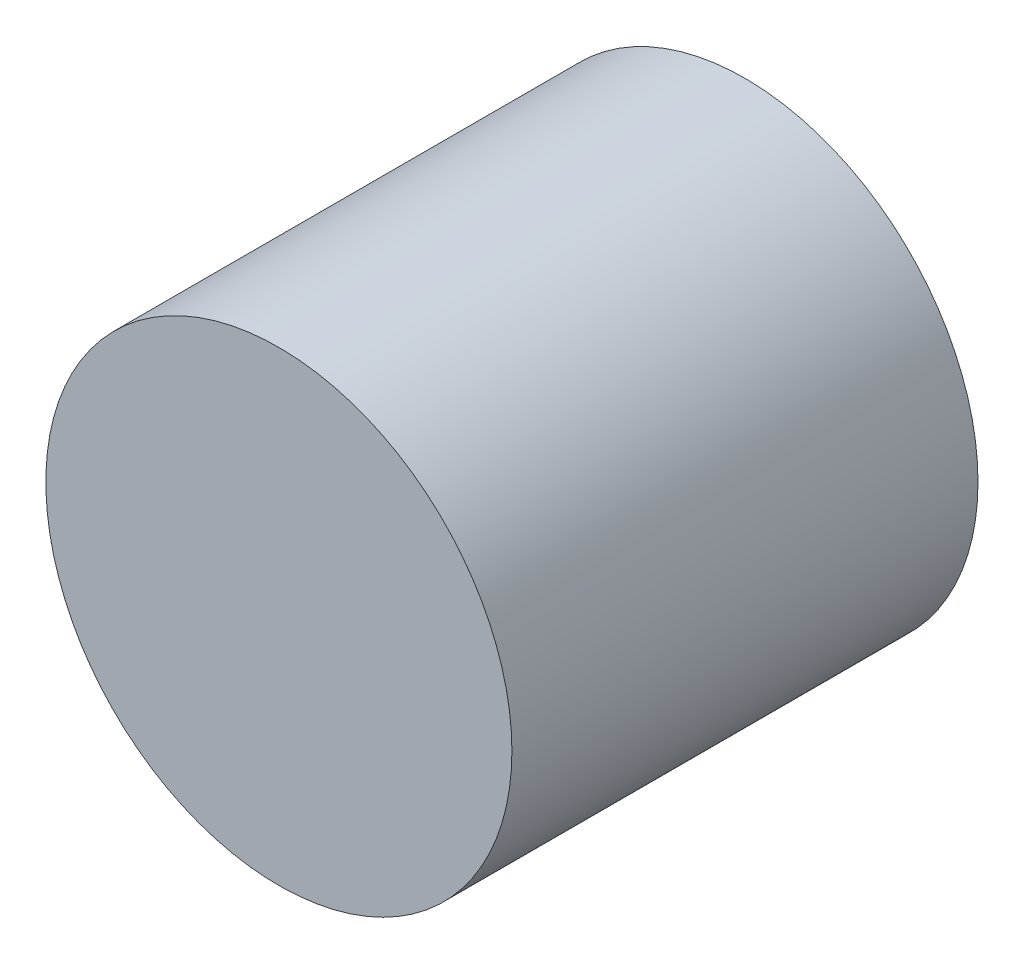
SolidWorks part; units mm, degrees
ref_plane "Front Plane" through (0, 0, 0) normal (0, 0, 1) x (1, 0, 0)
ref_plane "Top Plane" through (0, 0, 0) normal (0, 1, 0) x (1, 0, 0)
ref_plane "Right Plane" through (0, 0, 0) normal (1, 0, 0) x (0, 0, -1)
sketch "Sketch2" plane through (0, 0, 0) normal (0, 0, 1) x (1, 0, 0)
  circle A1 centre (0, 0) radius 7.9375
  dimension "outer_diameter" = 15.875
extrude "cylinder" add sketch "Sketch2" along normal blind 15.875
